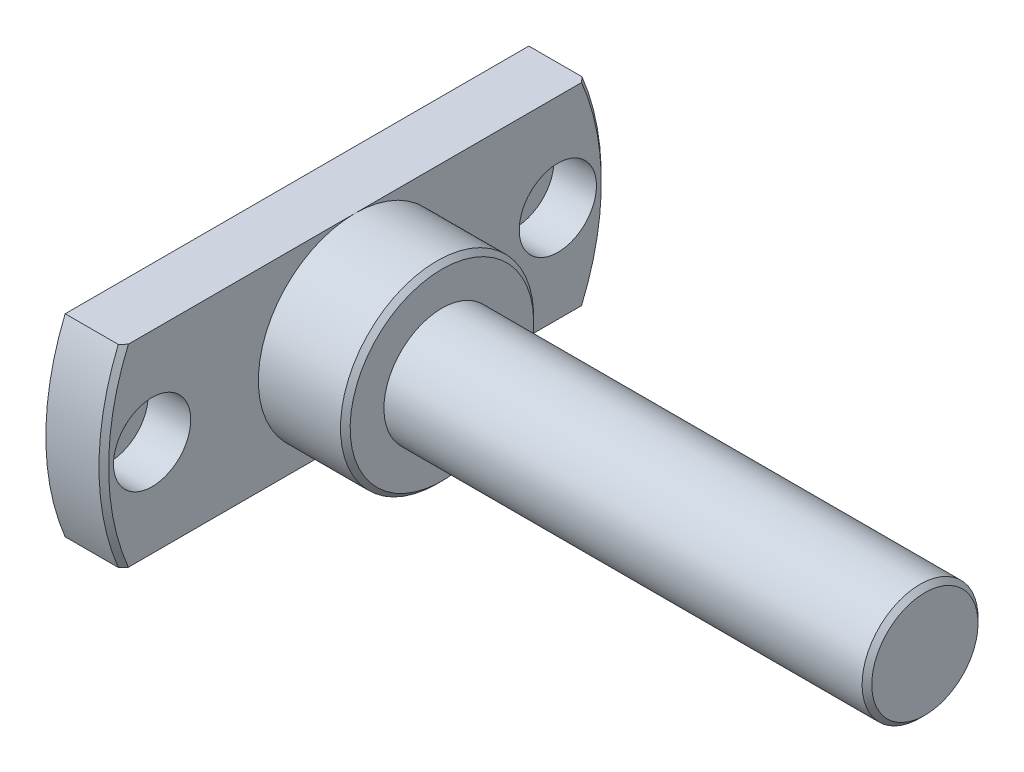
SolidWorks part; units mm, degrees
material "3.1325 (EN-AW 2017A)"
ref_plane "Plan de face" through (0, 0, 0) normal (0, 0, 1) x (1, 0, 0)
ref_plane "Plan de dessus" through (0, 0, 0) normal (0, 1, 0) x (1, 0, 0)
ref_plane "Plan de droite" through (0, 0, 0) normal (1, 0, 0) x (0, 0, -1)
sketch "Esquisse1" plane through (0, 0, 0) normal (0, 0, 1) x (1, 0, 0)
  line L0 (15, 6) -> (65, 6)
  line L1 (65, 6) -> (65, 0)
  line L2 (65, 0) -> (0, 0)
  line L3 (0, 0) -> (0, 26)
  line L4 (6, 10) -> (15, 10)
  line L5 (15, 10) -> (15, 6)
  line L7 (0, 26) -> (6, 26)
  line L8 (6, 26) -> (6, 10)
  dimension "D1" = 65
  dimension "D3" = 6
  dimension "D4" = 15
  dimension "D5" = 6
  dimension "D6" = 10
  dimension "D7" = 20
revolve "Révolution1" add sketch "Esquisse1" angle 360 about L2
chamfer "Chanfrein1" distance 0.5 angle 45 2 edges at (15, 10, 0) (6, 26, 0)
hole_wizard "Chambrage pour vis à tête hexagonale M41" positions "Esquisse4" profile "Esquisse2" counterbore size "M4" standard "ISO" end condition through all
sketch "Esquisse4" plane through (6, 0, 0) normal (1, 0, 0) x (0, 0, -1)
  line L0 (21, 0) -> (0, 0) construction
  line L1 (0, 0) -> (-21, 0) construction
  line L2 (0, 5.6863) -> (0, -6.4906) construction
  point P0 (-21, 0)
  point P2 (21, 0)
  dimension "D1" = 42
sketch "Esquisse2" plane through (6, 0, 21) normal (0, 1, 0) x (0, 0, -1)
  line L0 (0, 0) -> (0, 6)
  line L1 (0, 6) -> (2.25, 6)
  line L3 (2.25, 6) -> (2.25, 4.4)
  line L4 (2.25, 4.4) -> (4, 4.4)
  line L5 (4, 4.4) -> (4, 0)
  line L7 (4, 0) -> (0, 0)
  line L11 (0, -6.35) -> (0, 107.95) construction
  dimension "Diamètre du perçage jusqu'au prochain" = 4.5
  dimension "Profondeur du perçage jusqu'au prochain" = 6
  dimension "Diamètre du chambrage" = 8
  dimension "Profondeur du chambrage" = 4.4
sketch "Esquisse9" plane through (6, 0, 0) normal (1, 0, 0) x (0, 0, -1)
  point P0 (-21, 0)
  point P1 (21, 0)
sketch "Esquisse10" plane through (65, 0, 0) normal (1, 0, 0) x (0, 0, -1)
  line L0 (0, 15.042) -> (0, -18.3339) construction
sketch "Esquisse11" plane through (0, 0, 0) normal (-1, 0, 0) x (0, 0, 1)
  line L0 (24, -10) -> (-24, -10)
  line L2 (-33.9621, 0) -> (34.1744, 0) construction
  line L3 (24, 10) -> (-24, 10)
  circle A0 centre (0, 0) radius 26 construction
  arc A1 (-24, -10) -> (24, -10) centre (0, 0) ccw
  arc A2 (-24, 10) -> (24, 10) centre (0, 0) cw
  dimension "D1" = 20
extrude "Enlèv. mat.-Extru.2" cut sketch "Esquisse11" against normal through all
chamfer "Chanfrein3" distance 0.5 angle 45 1 edges at (65, 6, 0)
